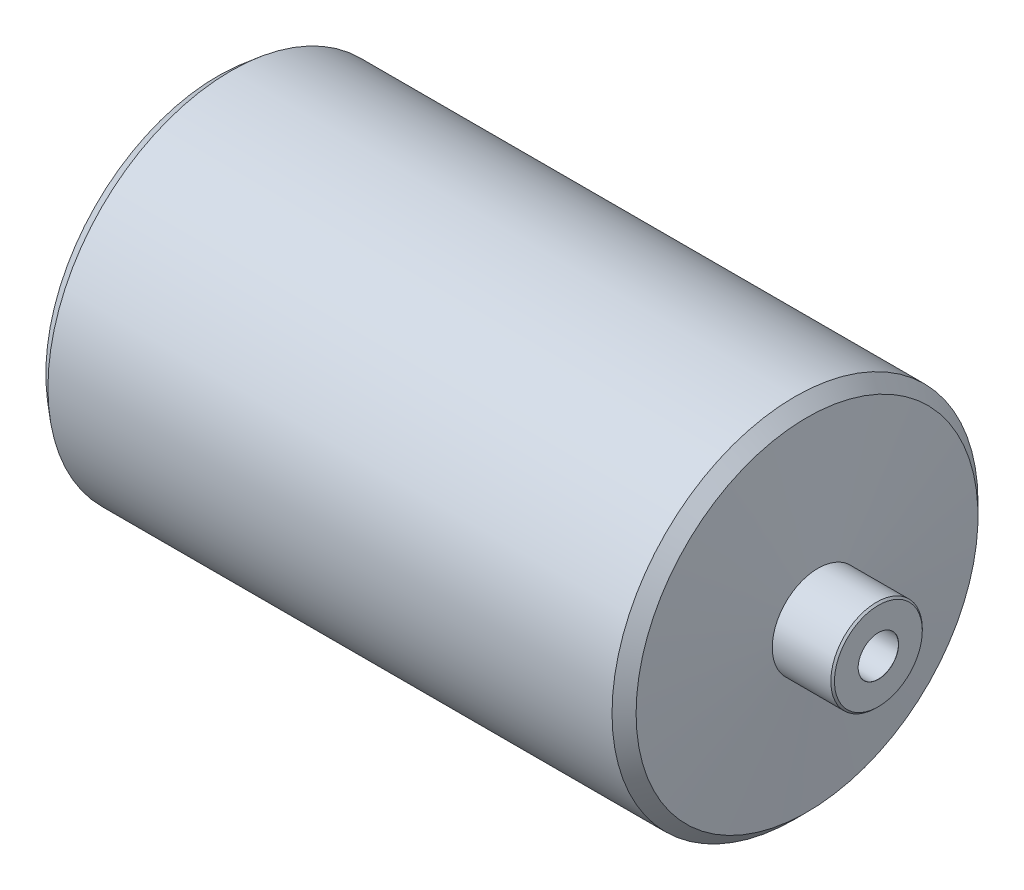
SolidWorks part; units mm, degrees
ref_plane "Front Plane" through (0, 0, 0) normal (0, 0, 1) x (1, 0, 0)
ref_plane "Top Plane" through (0, 0, 0) normal (0, 1, 0) x (1, 0, 0)
ref_plane "Right Plane" through (0, 0, 0) normal (1, 0, 0) x (0, 0, -1)
sketch "Sketch1" plane through (0, 0, 0) normal (0, 1, 0) x (1, 0, 0)
  line L0 (0, 0) -> (0, 12.5)
  line L1 (0, 12.5) -> (16.5, 12.5)
  line L2 (16.5, 12.5) -> (19.7808, 50)
  line L3 (19.7808, 50) -> (180.2192, 50)
  line L4 (180.2192, 50) -> (183.5, 12.5)
  line L5 (183.5, 12.5) -> (200, 12.5)
  line L6 (200, 12.5) -> (200, 0)
  line L7 (200, 0) -> (0, 0)
  dimension "D1" = 200
  dimension "D2" = 85
  dimension "D3" = 85
  dimension "D4" = 12.5
  dimension "D5" = 50
  dimension "D6" = 16.5
revolve "Revolve1" add sketch "Sketch1" angle 360 about L7
chamfer "Chamfer1" distance 3 angle 45 2 edges at (180.2192, 0, -50) (19.7808, 0, -50)
chamfer "Chamfer2" distance 0.5 angle 45 2 edges at (200, 0, -12.5) (0, 0, -12.5)
hole_wizard "M10 Clearance Hole1" positions "Sketch2" profile "Sketch3" hole size "M10" standard "ANSI Metric"
sketch "Sketch2" plane through (200, 0, 0) normal (1, 0, 0) x (0, 0, -1)
  point P0 (0, 0)
sketch "Sketch3" plane through (200, 0, 0) normal (0, 1, 0) x (0, 0, -1)
  line L0 (0, 0) -> (0, 59)
  line L1 (0, 59) -> (5.5, 55.6953)
  line L2 (5.5, 55.6953) -> (5.5, 0.025)
  line L3 (5.5, 0.025) -> (5.525, 0)
  line L5 (5.525, 0) -> (0, 0)
  line L6 (-5.5, 0.025) -> (-5.525, 0) construction
  line L10 (0, 59) -> (-5.5, 55.6953) construction
  line L11 (0, -6.35) -> (0, 107.95) construction
  dimension "Hole Dia." = 11
  dimension "Hole Depth" = 59
  dimension "Near C'Sink Dia." = 11.05
  dimension "Near C'Sink Angle" = 90
  dimension "Drill Angle" = 118
ref_plane "Plane1" through (100, 0, 0) normal (1, 0, 0) x (0, 0, -1)
mirror "Mirror1" about plane through (100, 0, 0) normal (1, 0, 0) of "M10 Clearance Hole1"
